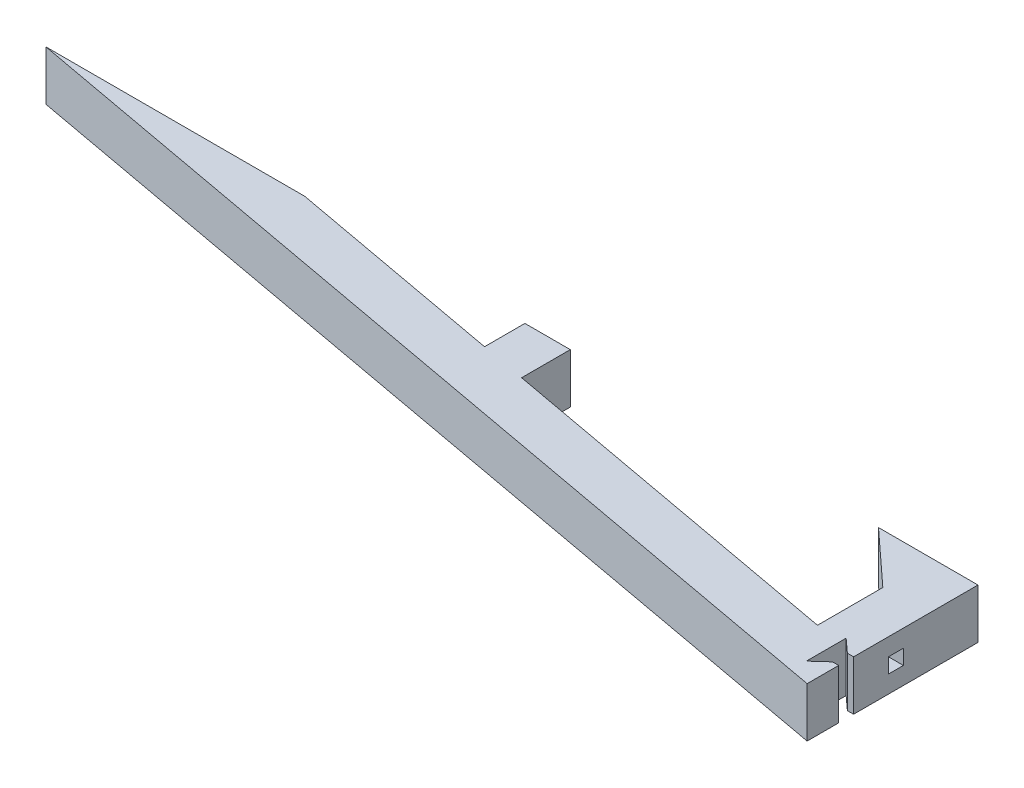
SolidWorks part; units mm, degrees
ref_plane "Přední rovina" through (0, 0, 0) normal (0, 0, 1) x (1, 0, 0)
ref_plane "Horní rovina" through (0, 0, 0) normal (0, 1, 0) x (1, 0, 0)
ref_plane "Pravá rovina" through (0, 0, 0) normal (1, 0, 0) x (0, 0, -1)
sketch "Skica2" plane through (0, 0, 0) normal (0, 1, 0) x (1, 0, 0)
  line L13 (0, 0) -> (0, -27.4721)
  line L14 (0, -27.4721) -> (-149.85, 0.0008)
  line L20 (-65.55, -7.8294) -> (-7.3, -18.5088)
  line L21 (-7.3, -18.5088) -> (-7.3, 0)
  line L22 (-7.3, 0) -> (0, 0)
  line L30 (-65.55, -7.8294) -> (-65.55, 0)
  line L31 (-65.55, 0) -> (-72.85, 0)
  line L32 (-72.85, 0) -> (-72.85, -6.4911)
  line L33 (-72.85, -6.4911) -> (-108.2597, 0.0008)
  line L34 (-108.2597, 0.0008) -> (-149.85, 0.0008)
  dimension "D1" = 27.4721
  dimension "D2" = 79.611
  dimension "D3" = 149.85
  dimension "D4" = 7.3
  dimension "D5" = 7.3
  dimension "D6" = 7.5
  dimension "D7" = 7.5
  dimension "D8" = 77
extrude "Přidat vysunutím1" add sketch "Skica2" along normal blind 8
sketch "Skica3" plane through (0, 8, 0) normal (0, 1, 0) x (1, 0, 0)
  line L6 (0, -20) -> (-1, -20)
  line L7 (0, -27.4721) -> (0, 0) construction
  line L8 (-1, -20) -> (-3.2, -18)
  line L9 (-3.2, -18) -> (-3.2, -24.4)
  line L10 (-3.2, -24.4) -> (-1, -22.4)
  line L11 (-1, -22.4) -> (0, -22.4)
  line L12 (0, -22.4) -> (0, -20)
  line L13 (0, 0) -> (-7.3, 0) construction
  dimension "D1" = 1
  dimension "D2" = 1
  dimension "D3" = 6.4
  dimension "D4" = 2.4
  dimension "D5" = 3.2
  dimension "D6" = 2
  dimension "40" = 18
extrude "Odebrat vysunutím1" cut sketch "Skica3" against normal through all
sketch "Skica5" plane through (0, 8, 0) normal (0, 1, 0) x (1, 0, 0)
  line L9 (0, 0) -> (-16, 0)
  line L16 (0, 0) -> (0, -8)
  line L17 (0, -8) -> (-16, -8)
  line L18 (-16, 0) -> (-16, -8)
  dimension "D1" = 8
  dimension "D2" = 16
extrude "Přidat vysunutím2" add sketch "Skica5" against normal blind 8
sketch "Skica7" plane through (0, 0, 0) normal (0, -1, 0) x (1, 0, 0)
  line L6 (-7.3, 8) -> (-16, 8)
  line L7 (-16, 8) -> (-16, 0)
  line L8 (-16, 0) -> (-7.3, 8)
extrude "Odebrat vysunutím4" cut sketch "Skica7" against normal through all
sketch "Skica4" plane through (0, 0, 0) normal (1, 0, 0) x (0, 0, -1)
  line L0 (-20, 8) -> (0, 8) construction
  line L5 (-14.4, 5.2) -> (-12, 5.2)
  line L6 (-14.4, 5.2) -> (-14.4, 2.8)
  line L7 (-14.4, 2.8) -> (-12, 2.8)
  line L8 (-12, 5.2) -> (-12, 2.8)
  line L13 (0, 8) -> (0, 0) construction
  dimension "D1" = 12
  dimension "D3" = 2.4
  dimension "D4" = 2.4
  dimension "D8" = 2.8
extrude "Odebrat vysunutím2" cut sketch "Skica4" against normal blind 4.4
sketch "Skica9" plane through (0, 0, 0) normal (0, 0, -1) x (-1, 0, 0)
  line L0 (65.55, 0) -> (72.85, 0) construction
  line L1 (0, 0) -> (16, 0) construction
  line L2 (0, 8) -> (0, 0) construction
  line L3 (65.55, 8) -> (65.55, 0) construction
  circle A0 centre (3.65, 4) radius 2.2
  circle A1 centre (69.2, 4) radius 2.2
  dimension "D1" = 4.4
  dimension "D2" = 4.4
  dimension "D3" = 4
  dimension "D4" = 4
  dimension "D5" = 3.65
  dimension "D6" = 3.65
extrude "Odebrat vysunutím5" cut sketch "Skica9" against normal blind 2.4
sketch "Skica10" plane through (0, 0, 2.4) normal (0, 0, -1) x (-1, 0, 0)
  circle A0 centre (3.65, 4) radius 1.85
  circle A1 centre (69.2, 4) radius 1.85
  dimension "D1" = 3.7
  dimension "D2" = 3.7
extrude "Odebrat vysunutím6" cut sketch "Skica10" against normal blind 7
